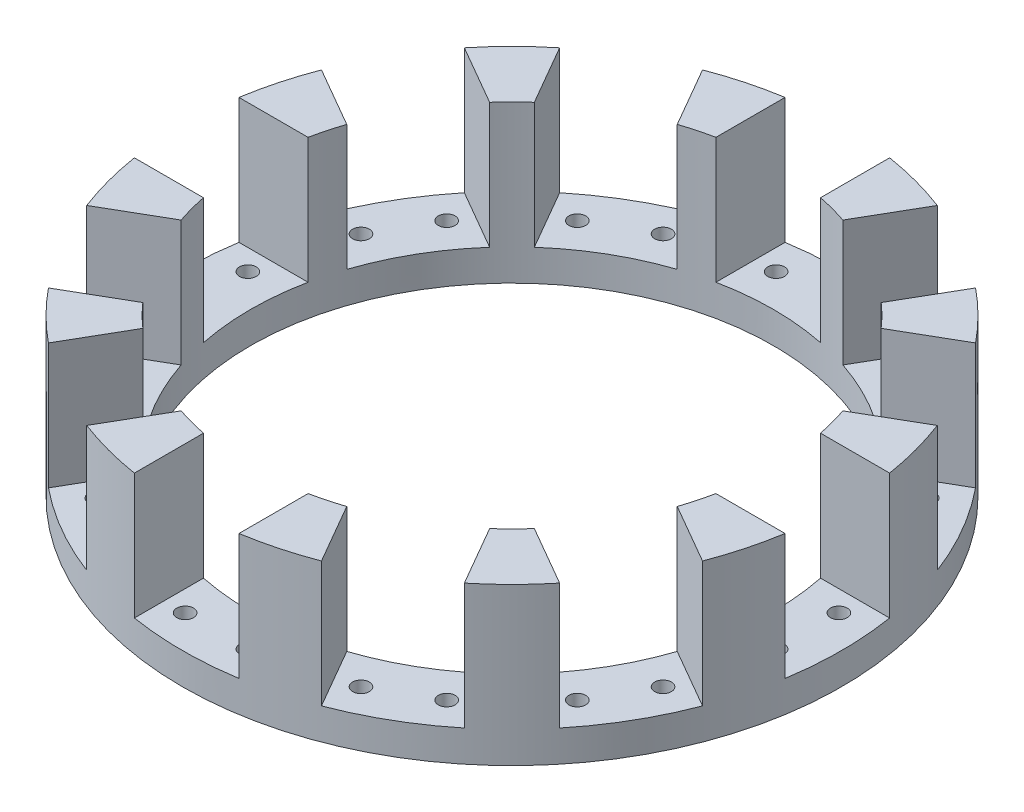
SolidWorks part; units mm, degrees
ref_plane "Front Plane" through (0, 0, 0) normal (0, 0, 1) x (1, 0, 0)
ref_plane "Top Plane" through (0, 0, 0) normal (0, 1, 0) x (1, 0, 0)
ref_plane "Right Plane" through (0, 0, 0) normal (1, 0, 0) x (0, 0, -1)
sketch "Sketch1" plane through (0, 0, 0) normal (0, 1, 0) x (1, 0, 0)
  circle A0 centre (0, 0) radius 125
  circle A1 centre (0, 0) radius 157.5
  dimension "D1" = 315
  dimension "D2" = 250
extrude "Boss-Extrude1" add sketch "Sketch1" along normal mid plane 75
sketch "Sketch2" plane through (0, 0, 0) normal (0, 0, 1) x (1, 0, 0)
  line L0 (-157.5, -37.5) -> (157.5, -37.5) construction
  line L1 (-25, -22.5) -> (25, -22.5)
  line L2 (-25, -22.5) -> (-25, 37.5)
  line L3 (-25, 37.5) -> (25, 37.5)
  line L4 (25, -22.5) -> (25, 37.5)
  line L5 (-25, -22.5) -> (25, 37.5) construction
  line L6 (-25, 37.5) -> (25, -22.5) construction
  point P0 (0, 7.5)
  dimension "D1" = 45
  dimension "D2" = 60
  dimension "D3" = 50
extrude "Cut-Extrude1" cut sketch "Sketch2" against normal through all both and the other way through all
pattern_circular "CirPattern1" count 12 over 360 about axis through (0, 0, 0) along (0, 1, 0) of "Cut-Extrude1"
sketch "Sketch3" plane through (0, -37.5, 0) normal (0, -1, 0) x (1, 0, 0)
  line L0 (0, -1000) -> (0, 49000) construction
  line L1 (-1000, 0) -> (49000, 0)
  circle A0 centre (-15, 141.25) radius 4
  circle A1 centre (15, 141.25) radius 4
  circle A2 centre (0, 0) radius 125 construction
  point P14 (0, 125)
  dimension "D1" = 8
  dimension "D2" = 8
  dimension "D3" = 30
  dimension "D4" = 16.25
  dimension "D5" = 142.0442
extrude "Cut-Extrude2" cut sketch "Sketch3" against normal through all
pattern_circular "CirPattern2" count 12 over 360 about axis through (0, 0, 0) along (0, 1, 0) of "Cut-Extrude2"
